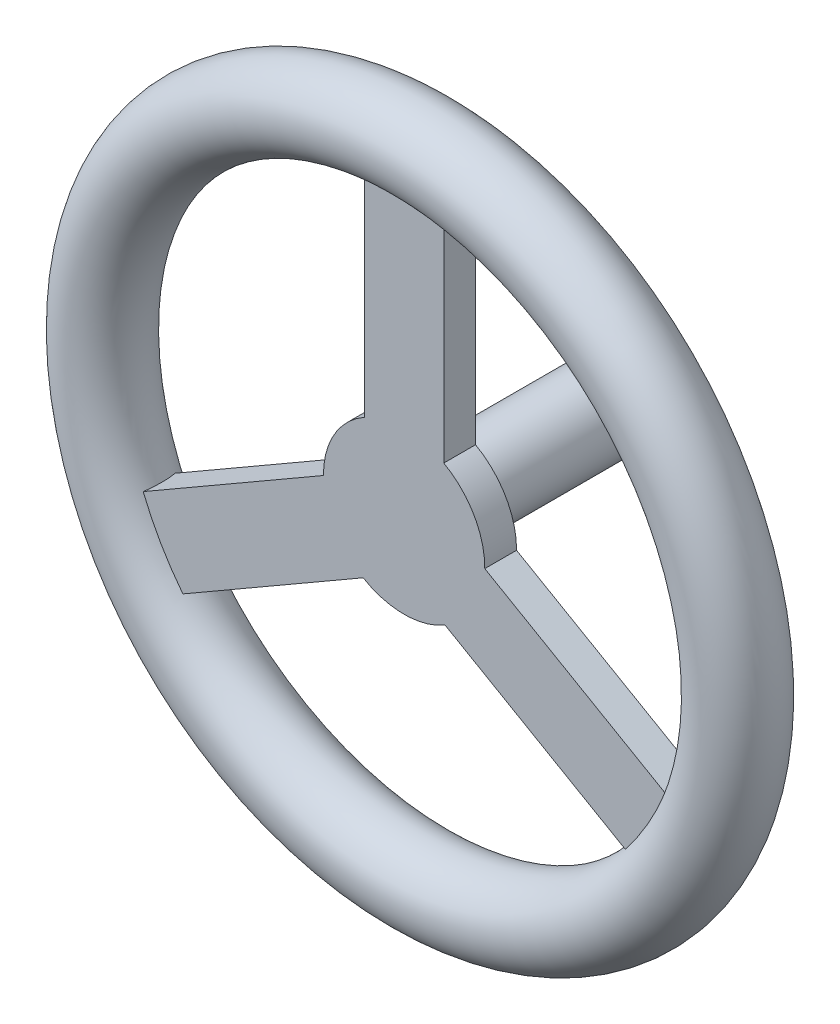
SolidWorks part; units mm, degrees
ref_plane "Front Plane" through (0, 0, 0) normal (0, 0, 1) x (1, 0, 0)
ref_plane "Top Plane" through (0, 0, 0) normal (0, 1, 0) x (1, 0, 0)
ref_plane "Right Plane" through (0, 0, 0) normal (1, 0, 0) x (0, 0, -1)
ref_axis "Axis1" through (0, 0, 0) along (0, 0, 1)
sketch "Sketch2" plane through (0, 0, 0) normal (0, 1, 0) x (1, 0, 0)
  line L0 (100, 0) -> (0, 0) construction
  circle A0 centre (100, 0) radius 12.5
  dimension "D1" = 100
  dimension "D2" = 25
revolve "Revolve1" add sketch "Sketch2" angle 360 about axis through (0, 0, 0) along (0, 0, 1)
sketch "Sketch3" plane through (0, 0, 0) normal (0, 0, 1) x (1, 0, 0)
  line L0 (-12.899, -21.881) -> (-25.399, -0.2303)
  line L1 (-12.899, -21.881) -> (-73.5207, -56.881)
  line L2 (-25.399, -0.2303) -> (-86.0207, -35.2303)
  line L3 (-73.5207, -56.881) -> (-86.0207, -35.2303)
  line L4 (25.399, -0.2303) -> (12.899, -21.881)
  line L5 (25.399, -0.2303) -> (86.0207, -35.2303)
  line L6 (12.899, -21.881) -> (73.5207, -56.881)
  line L7 (86.0207, -35.2303) -> (73.5207, -56.881)
  line L8 (-12.5, 22.1113) -> (12.5, 22.1113)
  line L9 (-12.5, 22.1113) -> (-12.5, 92.1113)
  line L10 (12.5, 22.1113) -> (12.5, 92.1113)
  line L11 (-12.5, 92.1113) -> (12.5, 92.1113)
  line L12 (-86.0207, -35.2303) -> (-12.5, 92.1113) construction
  line L13 (86.0207, -35.2303) -> (12.5, 92.1113) construction
  line L14 (-73.5207, -56.881) -> (73.5207, -56.881) construction
  circle A0 centre (0, 0) radius 25.4
  dimension "D1" = 50.8
  dimension "D2" = 25
  dimension "D3" = 70
extrude "Boss-Extrude1" add sketch "Sketch3" along normal mid plane 10 contours A0 L2 L3 L1 | L8 A0 L0 L4 | L0 A0 | L8 A0 | A0 L10 L11 L9 | L4 A0 | A0 L6 L7 L5
sketch "Sketch4" plane through (0, 0, -5) normal (0, 0, -1) x (-1, 0, 0)
  circle A0 centre (0, 0) radius 12.5
  dimension "D1" = 25
extrude "Boss-Extrude2" add sketch "Sketch4" along normal blind 50
